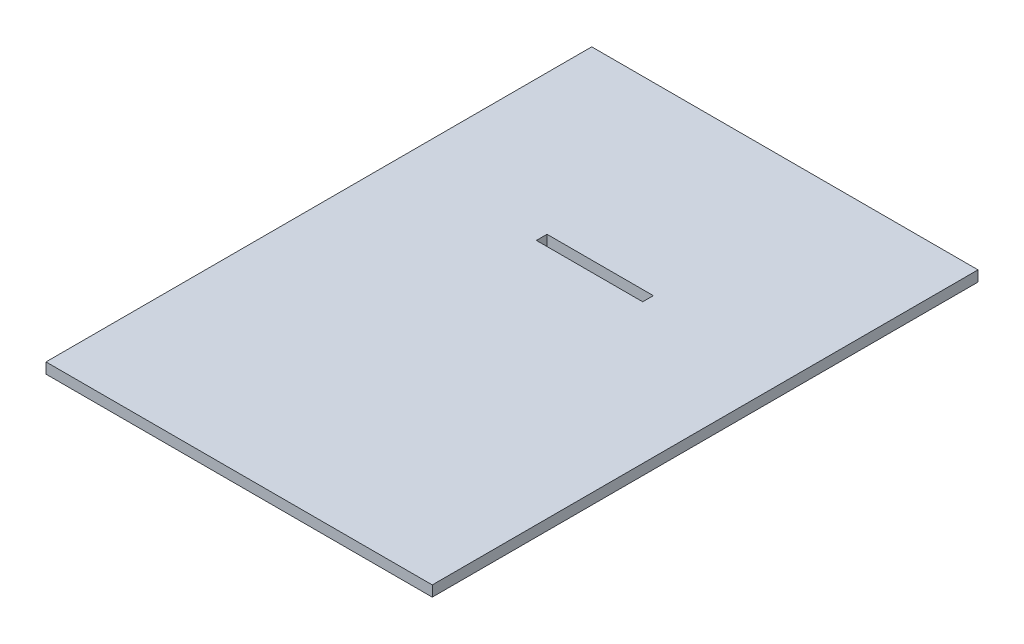
SolidWorks part; units mm, degrees
ref_plane "Front Plane" through (0, 0, 0) normal (0, 0, 1) x (1, 0, 0)
ref_plane "Top Plane" through (0, 0, 0) normal (0, 1, 0) x (1, 0, 0)
ref_plane "Right Plane" through (0, 0, 0) normal (1, 0, 0) x (0, 0, -1)
sketch "Sketch1" plane through (0, 0, 0) normal (0, 1, 0) x (1, 0, 0)
  line L1 (0, 0) -> (109, 0)
  line L2 (0, 0) -> (0, 154)
  line L3 (0, 154) -> (109, 154)
  line L4 (109, 0) -> (109, 154)
  dimension "D1" = 109
  dimension "D2" = 154
extrude "Boss-Extrude1" add sketch "Sketch1" along normal blind 3 contours L4 L3 L2 L1
sketch "Sketch2" plane through (0, 3, 0) normal (0, 1, 0) x (1, 0, 0)
  line L0 (0, 154) -> (109, 154) construction
  line L1 (39.5, 98.88) -> (69.5, 98.88)
  line L2 (39.5, 98.88) -> (39.5, 101.88)
  line L3 (39.5, 101.88) -> (69.5, 101.88)
  line L4 (69.5, 98.88) -> (69.5, 101.88)
  line L5 (54.5, 154) -> (54.5, 0) construction
  line L6 (0, 0) -> (109, 0) construction
  point P6 (0, 0)
  dimension "D1" = 55.12
  dimension "D2" = 3
  dimension "D3" = 30
extrude "Cut-Extrude1" cut sketch "Sketch2" against normal blind 3
